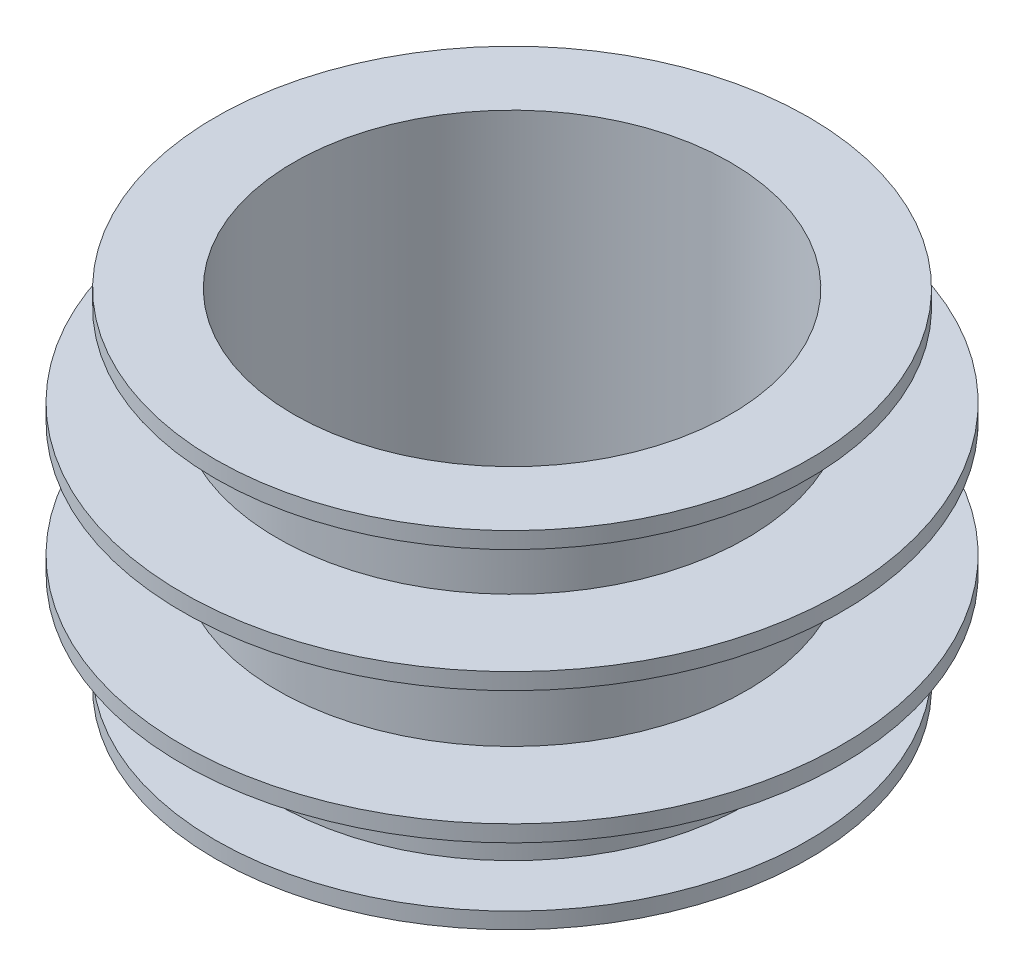
SolidWorks part; units mm, degrees
ref_plane "前视基准面" through (0, 0, 0) normal (0, 0, 1) x (1, 0, 0)
ref_plane "上视基准面" through (0, 0, 0) normal (0, 1, 0) x (1, 0, 0)
ref_plane "右视基准面" through (0, 0, 0) normal (1, 0, 0) x (0, 0, -1)
other "Configuration Table"
sketch "草图1" plane through (0, 0, 0) normal (0, 0, 1) x (1, 0, 0)
  line L0 (0, 0) -> (0, 20.9799) construction
  line L1 (11.8811, 20.9799) -> (18, 20.9799)
  line L2 (18, 20.9799) -> (18, 19.9799)
  line L3 (18, 19.9799) -> (14.25, 19.9799)
  line L4 (14.25, 19.9799) -> (14.25, 14.9799)
  line L5 (14.25, 14.9799) -> (20, 14.9799)
  line L6 (20, 14.9799) -> (20, 13.9799)
  line L7 (20, 13.9799) -> (14.25, 13.9799)
  line L8 (14.25, 13.9799) -> (14.25, 6.9799)
  line L9 (14.25, 6.9799) -> (20, 6.9799)
  line L10 (20, 6.9799) -> (20, 5.9799)
  line L11 (20, 5.9799) -> (14.25, 5.9799)
  line L12 (14.25, 5.9799) -> (14.25, 0.9799)
  line L13 (14.25, 0.9799) -> (18, 0.9799)
  line L14 (18, 0.9799) -> (18, 0)
  line L15 (18, 0) -> (4.6482, 0)
  line L16 (0, 20.9799) -> (11.8811, 20.9799)
  line L17 (0, 0) -> (4.6482, 0)
  line L18 (0, 0) -> (0, 20.9799)
  dimension "D1" = 1
  dimension "D2" = 5
  dimension "D3" = 1
  dimension "D4" = 7
  dimension "D5" = 1
  dimension "D6" = 5
  dimension "D7" = 0.9799
  dimension "D8" = 28.5
  dimension "D9" = 36
  dimension "D10" = 40
revolve "旋转1" add sketch "草图1" angle 360 about L0
sketch "草图2" plane through (0, 20.9799, 0) normal (0, 1, 0) x (1, 0, 0)
  circle A0 centre (0, 0) radius 13.25
  dimension "D1" = 26.5
extrude "切除-拉伸1" cut sketch "草图2" against normal through all
